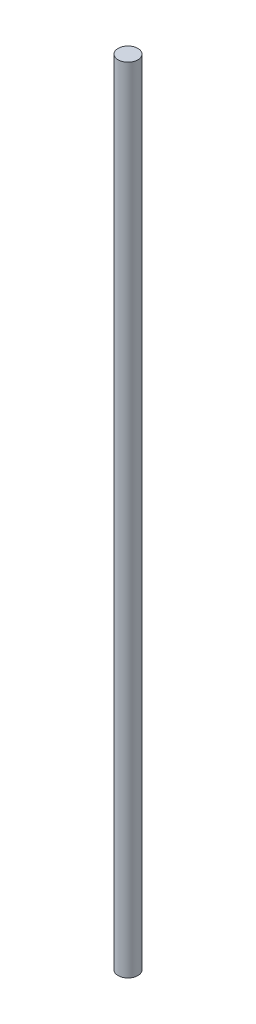
SolidWorks part; units mm, degrees
material "Custom Plastic"
ref_plane "Front Plane" through (0, 0, 0) normal (0, 0, 1) x (1, 0, 0)
ref_plane "Top Plane" through (0, 0, 0) normal (0, 1, 0) x (1, 0, 0)
ref_plane "Right Plane" through (0, 0, 0) normal (1, 0, 0) x (0, 0, -1)
sketch "Sketch2" plane through (0, 0, 0) normal (0, 1, 0) x (1, 0, 0)
  circle A0 centre (0, 0) radius 1.5
  dimension "D1" = 3
extrude "WaterWheelAxel" add sketch "Sketch2" along normal blind 120
